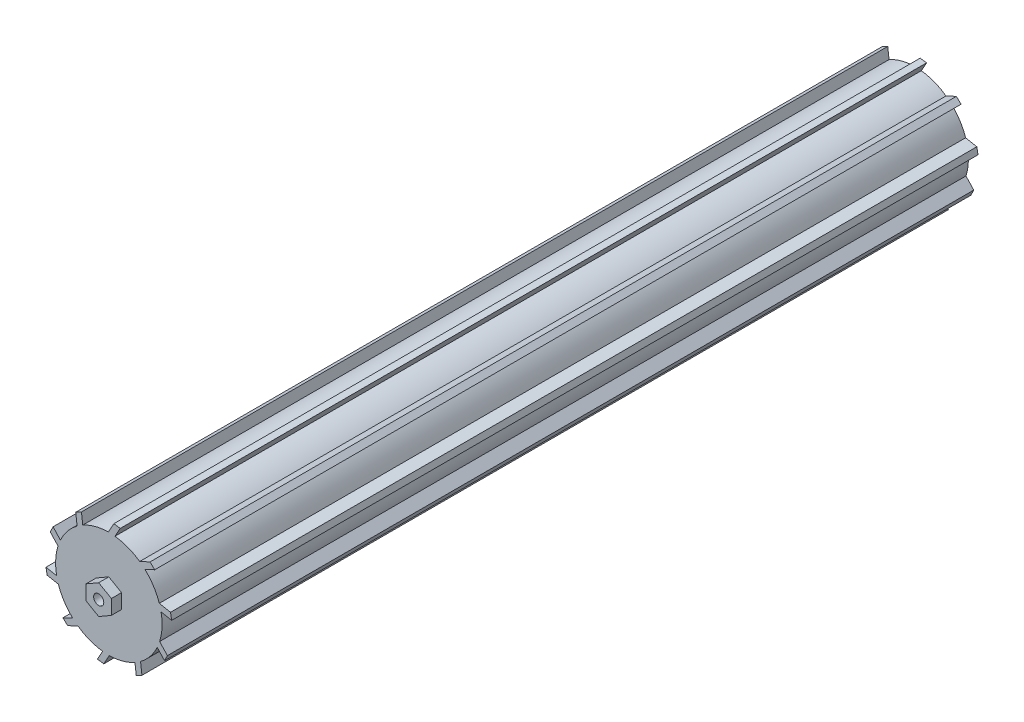
SolidWorks part; units mm, degrees
material "Rubber"
ref_plane "Front Plane" through (0, 0, 0) normal (0, 0, 1) x (1, 0, 0)
ref_plane "Top Plane" through (0, 0, 0) normal (0, 1, 0) x (1, 0, 0)
ref_plane "Right Plane" through (0, 0, 0) normal (1, 0, 0) x (0, 0, -1)
sketch "Sketch1" plane through (0, 0, 0) normal (0, 0, 1) x (1, 0, 0)
  circle A0 centre (0, 0) radius 10.5
  dimension "D1" = 21
extrude "Boss-Extrude1" add sketch "Sketch1" along normal mid plane 153
sketch "Sketch3" plane through (0, 0, -76.5) normal (0, 0, -1) x (-1, 0, 0)
  line L0 (0, -9.5) -> (0, 9.5) construction
  line L1 (-1.5, -1.5) -> (1.5, -1.5)
  line L2 (-1.5, -1.5) -> (-1.5, 1.5)
  line L3 (-1.5, 1.5) -> (1.5, 1.5)
  line L4 (1.5, -1.5) -> (1.5, 1.5)
  line L5 (-1.5, -1.5) -> (1.5, 1.5) construction
  line L6 (-1.5, 1.5) -> (1.5, -1.5) construction
  line L7 (-9.5, 0) -> (9.5, 0) construction
  point P0 (0.4316, -0.1292)
  point P8 (0, 0)
  point P11 (0, 0)
  dimension "D1" = 3
  dimension "D2" = 3
extrude "Boss-Extrude2" add sketch "Sketch3" along normal blind 12
sketch "Sketch4" plane through (0, 0, 76.5) normal (0, 0, 1) x (1, 0, 0)
  line L1 (0, 2.8868) -> (-2.5, 1.4434)
  line L2 (-2.5, 1.4434) -> (-2.5, -1.4434)
  line L3 (-2.5, -1.4434) -> (0, -2.8868)
  line L4 (0, -2.8868) -> (2.5, -1.4434)
  line L5 (2.5, -1.4434) -> (2.5, 1.4434)
  line L6 (2.5, 1.4434) -> (0, 2.8868)
  circle A0 centre (0, 0) radius 2.5 construction
  circle A1 centre (0, 0) radius 1
  dimension "D1" = 5
  dimension "D2" = 2
extrude "Boss-Extrude3" add sketch "Sketch4" along normal blind 2
sketch "Sketch7" plane through (0, 0, -76.5) normal (0, 0, -1) x (-1, 0, 0)
  line L1 (-1.5, -1.5) -> (1.5, -1.5)
  line L2 (-1.5, -1.5) -> (-1.5, 1.5)
  line L3 (-1.5, 1.5) -> (1.5, 1.5)
  line L4 (1.5, -1.5) -> (1.5, 1.5)
  line L5 (-1.5, -1.5) -> (1.5, 1.5) construction
  line L6 (-1.5, 1.5) -> (1.5, -1.5) construction
  circle A0 centre (0, 0) radius 10.5
  dimension "D1" = 21
extrude "Boss-Extrude4" add sketch "Sketch7" along normal blind 6
sketch "Sketch8" plane through (0, 0, 76.5) normal (0, 0, 1) x (1, 0, 0)
  line L0 (-0.2289, 10.2794) -> (0.9856, 12.4632)
  line L1 (0.9856, 12.4632) -> (2.2535, 12.2952)
  line L2 (2.2535, 12.2952) -> (1.0363, 10.1065)
  line L3 (-0.2289, 10.2794) -> (1.0363, 10.1065)
  line L4 (9.0501, 8.6224) -> (6.7788, 7.5672)
  line L5 (8.1231, 9.5036) -> (9.0501, 8.6224)
  line L6 (5.8569, 8.4508) -> (8.1231, 9.5036)
  line L7 (5.8569, 8.4508) -> (6.7788, 7.5672)
  line L8 (12.3898, 1.6562) -> (9.9321, 2.1375)
  line L9 (12.1578, 2.914) -> (12.3898, 1.6562)
  line L10 (9.7056, 3.3942) -> (12.1578, 2.914)
  line L11 (9.7056, 3.3942) -> (9.9321, 2.1375)
  line L12 (10.9971, -5.9426) -> (9.2916, -4.1086)
  line L13 (11.5486, -4.7887) -> (10.9971, -5.9426)
  line L14 (9.847, -2.9588) -> (11.5486, -4.7887)
  line L15 (9.847, -2.9588) -> (9.2916, -4.1086)
  line L16 (5.4038, -11.2716) -> (5.1021, -8.7854)
  line L17 (6.5283, -10.6623) -> (5.4038, -11.2716)
  line L18 (6.2273, -8.1817) -> (6.5283, -10.6623)
  line L19 (6.2273, -8.1817) -> (5.1021, -8.7854)
  line L20 (-2.2535, -12.2952) -> (-1.0363, -10.1065)
  line L21 (-0.9856, -12.4632) -> (-2.2535, -12.2952)
  line L22 (0.2289, -10.2794) -> (-0.9856, -12.4632)
  line L23 (0.2289, -10.2794) -> (-1.0363, -10.1065)
  line L24 (-9.0501, -8.6224) -> (-6.7788, -7.5672)
  line L25 (-8.1231, -9.5036) -> (-9.0501, -8.6224)
  line L26 (-5.8569, -8.4508) -> (-8.1231, -9.5036)
  line L27 (-5.8569, -8.4508) -> (-6.7788, -7.5672)
  line L28 (-12.3898, -1.6562) -> (-9.9321, -2.1375)
  line L29 (-12.1578, -2.914) -> (-12.3898, -1.6562)
  line L30 (-9.7056, -3.3942) -> (-12.1578, -2.914)
  line L31 (-9.7056, -3.3942) -> (-9.9321, -2.1375)
  line L32 (-10.9971, 5.9426) -> (-9.2916, 4.1086)
  line L33 (-11.5486, 4.7887) -> (-10.9971, 5.9426)
  line L34 (-9.847, 2.9588) -> (-11.5486, 4.7887)
  line L35 (-9.847, 2.9588) -> (-9.2916, 4.1086)
  line L36 (-5.4038, 11.2716) -> (-5.1021, 8.7854)
  line L37 (-6.5283, 10.6623) -> (-5.4038, 11.2716)
  line L38 (-6.2273, 8.1817) -> (-6.5283, 10.6623)
  line L39 (-6.2273, 8.1817) -> (-5.1021, 8.7854)
  circle A2 centre (0, 0) radius 12.5
  circle A3 centre (0, 0) radius 12.5 construction
  point P45 (0, 0)
  dimension "D1" = 2
  dimension "D2" = 10
extrude "Boss-Extrude5" add sketch "Sketch8" against normal up to surface (159 mm away) up to face at (-10.5, 0, -82.5)
